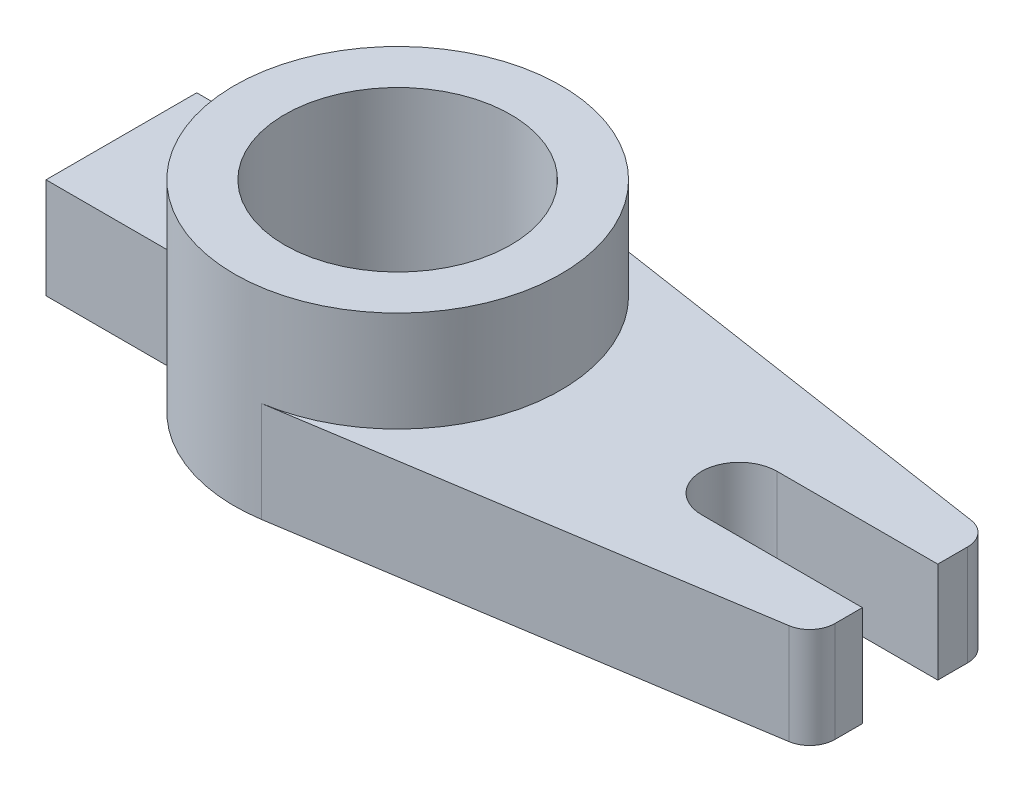
SolidWorks part; units mm, degrees
ref_plane "Płaszczyzna przednia" through (0, 0, 0) normal (0, 0, 1) x (1, 0, 0)
ref_plane "Płaszczyzna górna" through (0, 0, 0) normal (0, 1, 0) x (1, 0, 0)
ref_plane "Płaszczyzna prawa" through (0, 0, 0) normal (1, 0, 0) x (0, 0, -1)
sketch "Szkic1" plane through (0, 0, 0) normal (0, 1, 0) x (1, 0, 0)
  circle A0 centre (0, 0) radius 22.5
  circle A1 centre (0, 0) radius 32.5
  dimension "D1" = 65
  dimension "D2" = 45
sketch "Szkic2" plane through (0, 0, 0) normal (0, 1, 0) x (1, 0, 0)
  line L0 (0, 0) -> (-55, 0) construction
  line L1 (-28.8314, 15) -> (-55, 15)
  line L2 (-55, 15) -> (-55, -15)
  line L3 (-55, -15) -> (-28.8314, -15)
  circle A0 centre (0, 0) radius 32.5 construction
  arc A1 (-28.8314, 15) -> (-28.8314, -15) centre (0, 0) ccw
  dimension "D3" = 32.5
  dimension "D1" = 30
  dimension "D2" = 55
sketch "Szkic3" plane through (0, 0, 0) normal (0, 1, 0) x (1, 0, 0)
  line L0 (0, 0) -> (100, 0) construction
  line L1 (4.8605, 32.1345) -> (95.7478, 18.3874)
  line L2 (100, 13.4437) -> (100, 7.5)
  line L3 (95.7726, -17.9169) -> (5.0217, -32.1097)
  line L4 (68, 7.5) -> (100, 7.5)
  line L5 (68, -7.5) -> (100, -7.5)
  line L6 (100, -7.5) -> (100, -12.9769)
  circle A0 centre (0, 0) radius 32.5 construction
  arc A1 (100, -12.9769) -> (95.7726, -17.9169) centre (95, -12.9769) cw
  arc A2 (100, 13.4437) -> (95.7478, 18.3874) centre (95, 13.4437) ccw
  arc A3 (68, 7.5) -> (68, -7.5) centre (68, 0) ccw
  arc A4 (4.8605, 32.1345) -> (5.0217, -32.1097) centre (0, 0) cw
  point P11 (100, -17.2557)
  point P14 (100, 17.7443)
  dimension "D2" = 5
  dimension "D5" = 100
  dimension "D6" = 7.5
  dimension "D1" = 35
  dimension "D3" = 32
  dimension "D4" = 15
  dimension "D7" = 91.854
extrude "Dodanie-wyciągnięcie1" add sketch "Szkic3" along normal blind 20
extrude "Dodanie-wyciągnięcie2" add sketch "Szkic1" along normal blind 40
extrude "Dodanie-wyciągnięcie3" add sketch "Szkic2" along normal blind 20
